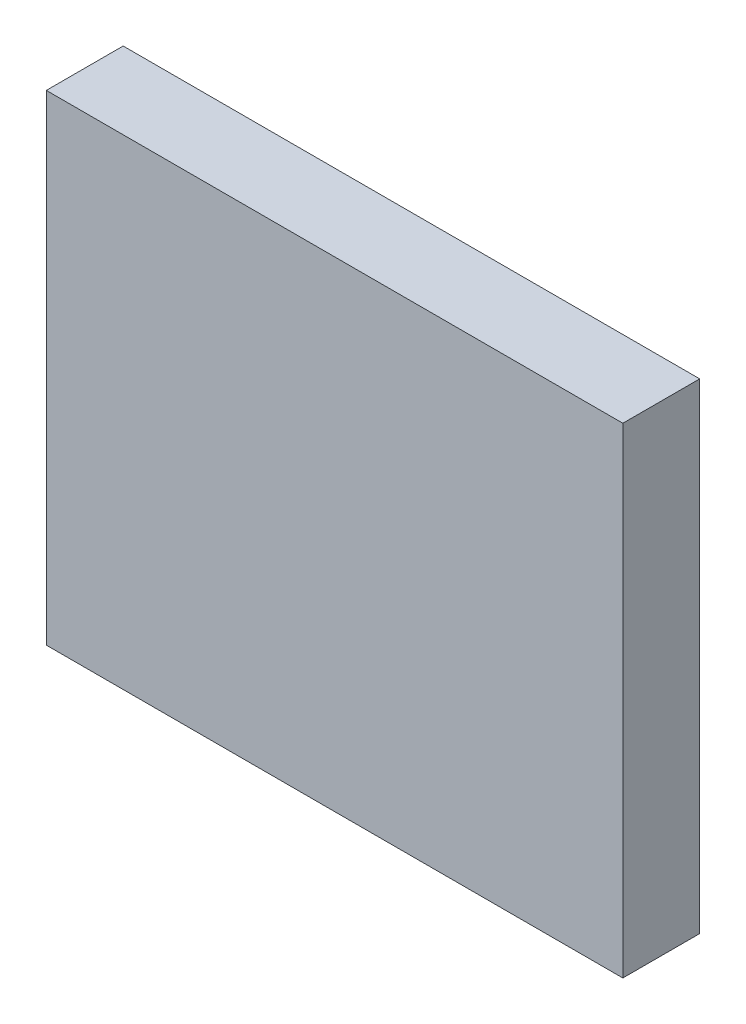
SolidWorks part; units mm, degrees
ref_plane "Piano frontale" through (0, 0, 0) normal (0, 0, 1) x (1, 0, 0)
ref_plane "Piano superiore" through (0, 0, 0) normal (0, 1, 0) x (1, 0, 0)
ref_plane "Piano destro" through (0, 0, 0) normal (1, 0, 0) x (0, 0, -1)
sketch "Schizzo1" plane through (0, 0, 0) normal (0, 0, 1) x (1, 0, 0)
  line L0 (0, 0) -> (30, 0)
  line L1 (30, 0) -> (30, 25)
  line L2 (0, 0) -> (0, 25)
  line L3 (0, 25) -> (30, 25)
  dimension "D1" = 30
  dimension "D2" = 25
extrude "Estrusione-Estrusione1" add sketch "Schizzo1" along normal blind 4
